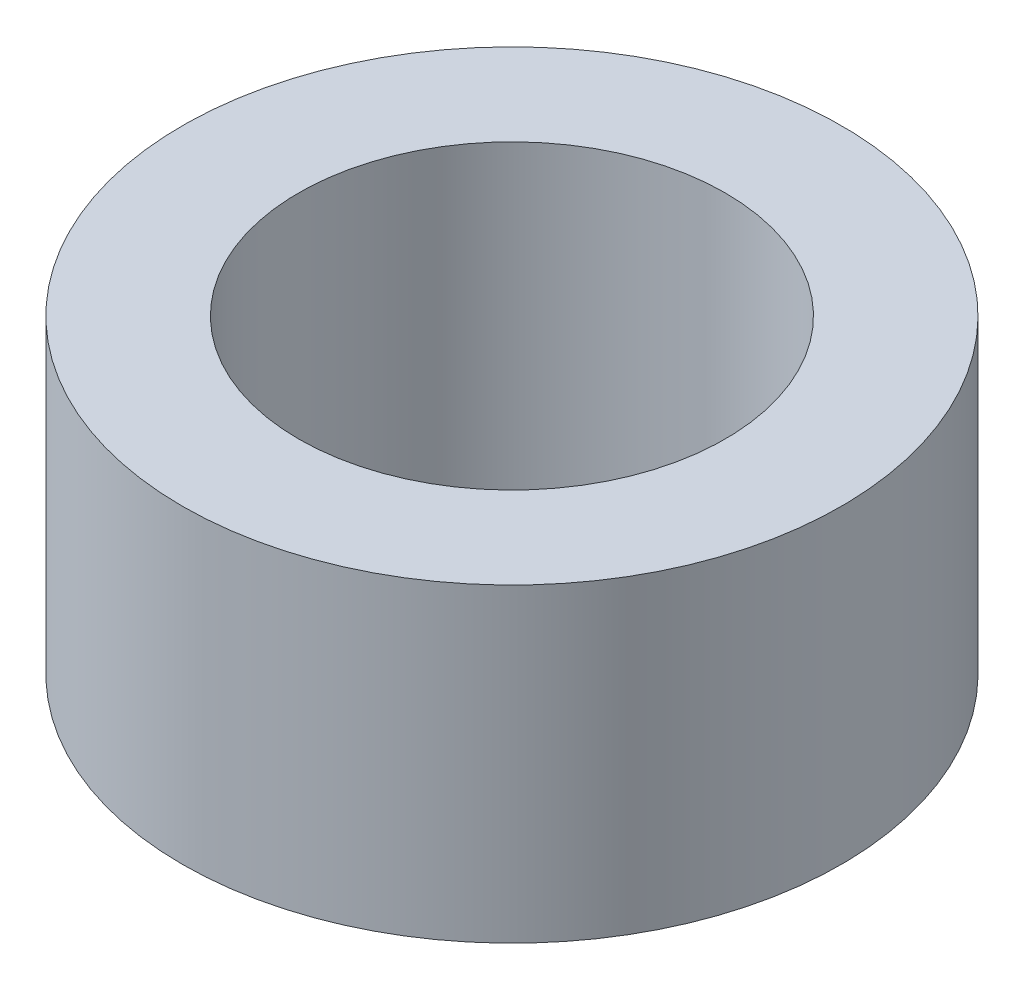
SolidWorks part; units mm, degrees
ref_plane "Front Plane" through (0, 0, 0) normal (0, 0, 1) x (1, 0, 0)
ref_plane "Top Plane" through (0, 0, 0) normal (0, 1, 0) x (1, 0, 0)
ref_plane "Right Plane" through (0, 0, 0) normal (1, 0, 0) x (0, 0, -1)
sketch "Sketch1" plane through (0, 0, 0) normal (0, 1, 0) x (1, 0, 0)
  circle A0 centre (0, 0) radius 2.75
  circle A1 centre (0, 0) radius 4.25
  dimension "D1" = 5.5
  dimension "D2" = 1.5
extrude "Boss-Extrude1" add sketch "Sketch1" along normal blind 4
